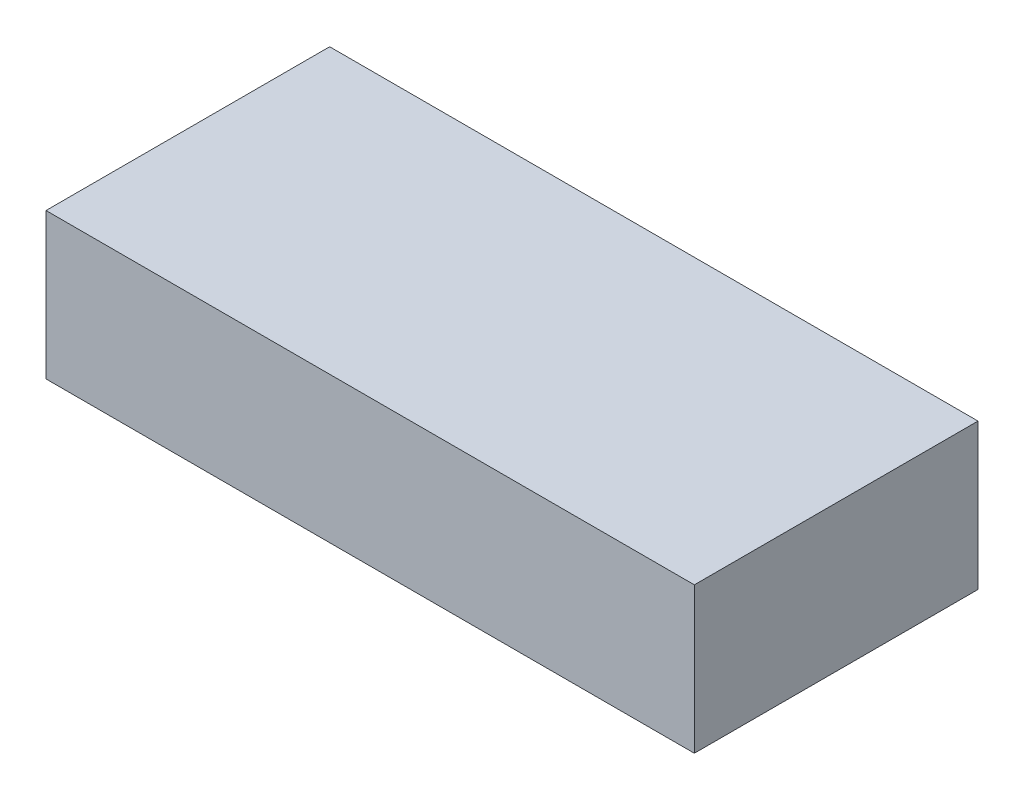
SolidWorks part; units mm, degrees
ref_plane "前视基准面" through (0, 0, 0) normal (0, 0, 1) x (1, 0, 0)
ref_plane "上视基准面" through (0, 0, 0) normal (0, 1, 0) x (1, 0, 0)
ref_plane "右视基准面" through (0, 0, 0) normal (1, 0, 0) x (0, 0, -1)
sketch "草图1" plane through (0, 0, 0) normal (0, 1, 0) x (1, 0, 0)
  line L1 (40, -17.5) -> (-40, -17.5)
  line L2 (40, -17.5) -> (40, 17.5)
  line L3 (40, 17.5) -> (-40, 17.5)
  line L4 (-40, -17.5) -> (-40, 17.5)
  line L5 (0, 17.5) -> (0, -17.5) construction
  line L6 (40, 0) -> (-40, 0) construction
  point P0 (0, 0)
extrude "凸台-拉伸1" add sketch "草图1" along normal blind 18
